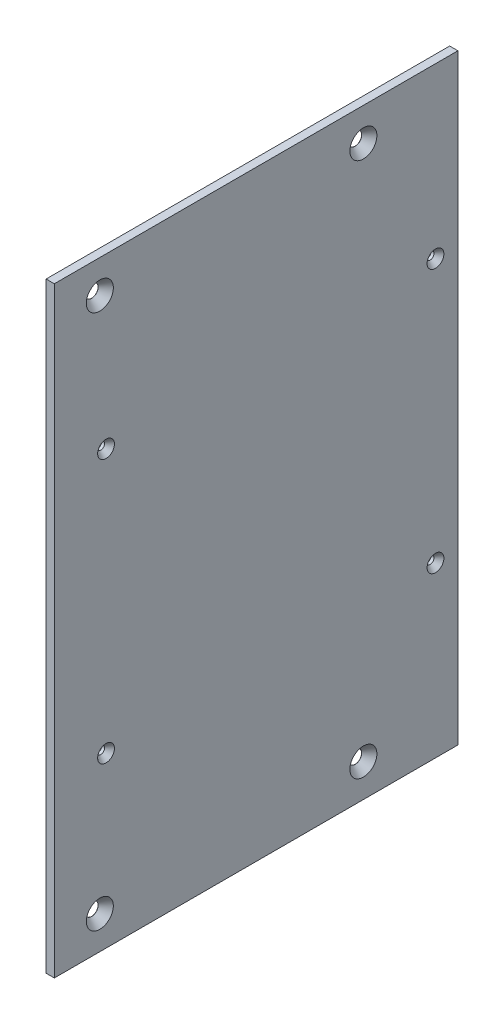
SolidWorks part; units mm, degrees
ref_plane "Front Plane" through (0, 0, 0) normal (0, 0, 1) x (1, 0, 0)
ref_plane "Top Plane" through (0, 0, 0) normal (0, 1, 0) x (1, 0, 0)
ref_plane "Right Plane" through (0, 0, 0) normal (1, 0, 0) x (0, 0, -1)
sketch "Sketch1" plane through (19.05, 0, 0) normal (1, 0, 0) x (0, 1, 0)
  line L0 (24.3095, 180.84) -> (-207.4655, 180.84)
  line L6 (-207.4655, 180.84) -> (-207.4655, 25.265)
  line L7 (-207.4655, 25.265) -> (24.3095, 25.265)
  line L8 (24.3095, 25.265) -> (24.3095, 180.84)
  dimension "D1" = 155.575
extrude "Boss-Extrude1" add sketch "Sketch1" along normal blind 3.175
sketch "Sketch9" plane through (22.225, 0, 12.573) normal (-1, 0, 0) x (0, 0, -1)
  line L1 (-21.3375, 142.378) -> (-21.3375, 40.778) construction
  line L2 (-21.3375, 40.778) -> (-148.3375, 40.778) construction
  line L3 (-148.3375, 40.778) -> (-148.3375, 142.378) construction
  line L4 (-148.3375, 142.378) -> (-21.3375, 142.378) construction
  point P0 (-148.3375, 142.378)
  dimension "D1" = 0
  dimension "D2" = 0
sketch "Sketch3" plane through (19.05, 0, 0) normal (-1, 0, 0) x (0, 1, 0)
  line L0 (11.6095, -163.3006) -> (11.6095, -61.7006) construction
  line L1 (11.6095, -61.7006) -> (-194.7655, -61.7006) construction
  line L2 (-194.7655, -61.7006) -> (-194.7655, -163.3006) construction
  line L3 (-194.7655, -163.3006) -> (11.6095, -163.3006) construction
  line L4 (-207.4655, -25.265) -> (24.3095, -25.265) construction
  dimension "D1" = 36.4356
hole_wizard "#10 Clearance Hole1" positions "Sketch4" profile "Sketch5" hole size "#10" standard "ANSI Inch" end condition through all
sketch "Sketch4" plane through (19.05, 0, 0) normal (-1, 0, 0) x (0, 1, 0)
  point P0 (-194.7655, -163.3006)
  point P3 (-194.7655, -61.7006)
  point P6 (11.6095, -61.7006)
  point P9 (11.6095, -163.3006)
sketch "Sketch5" plane through (19.05, -194.7655, 163.3006) normal (0, 1, 0) x (0, 0, 1)
  line L0 (0, 0) -> (0, 3.175)
  line L1 (0, 3.175) -> (5.207, 3.175)
  line L2 (2.4892, 0.0485) -> (2.4892, 0)
  line L5 (2.4892, 0) -> (0, 0)
  line L7 (5.207, 3.175) -> (2.4892, 0.0485)
  line L8 (-5.207, 3.175) -> (-2.4892, 0.0485) construction
  line L11 (0, -6.35) -> (0, 107.95) construction
  dimension "Thru Hole Dia." = 4.9784
  dimension "Thru Hole Depth" = 3.175
  dimension "Far C'Sink Dia." = 10.414
  dimension "Far C'Sink Angle" = 82
hole_wizard "#4 Clearance Hole1" positions "Sketch10" profile "Sketch11" hole size "#4" standard "ANSI Inch" end condition through all
sketch "Sketch10" plane through (22.225, 0, 0) normal (1, 0, 0) x (0, -1, 0)
  point P0 (40.778, -160.9105)
  point P3 (142.378, -160.9105)
  point P6 (142.378, -33.9105)
  point P9 (40.778, -33.9105)
sketch "Sketch11" plane through (22.225, -40.778, 160.9105) normal (0, 1, 0) x (0, 0, -1)
  line L0 (0, 0) -> (0, 3.175)
  line L1 (0, 3.175) -> (1.4732, 3.175)
  line L2 (1.4732, 3.175) -> (1.4732, 2.0307)
  line L3 (1.4732, 2.0307) -> (3.2385, 0)
  line L5 (3.2385, 0) -> (0, 0)
  line L6 (-1.4732, 2.0307) -> (-3.2385, 0) construction
  line L11 (0, -6.35) -> (0, 107.95) construction
  dimension "Thru Hole Dia." = 2.9464
  dimension "Thru Hole Depth" = 3.175
  dimension "Near C'Sink Dia." = 6.477
  dimension "Near C'Sink Angle" = 82
